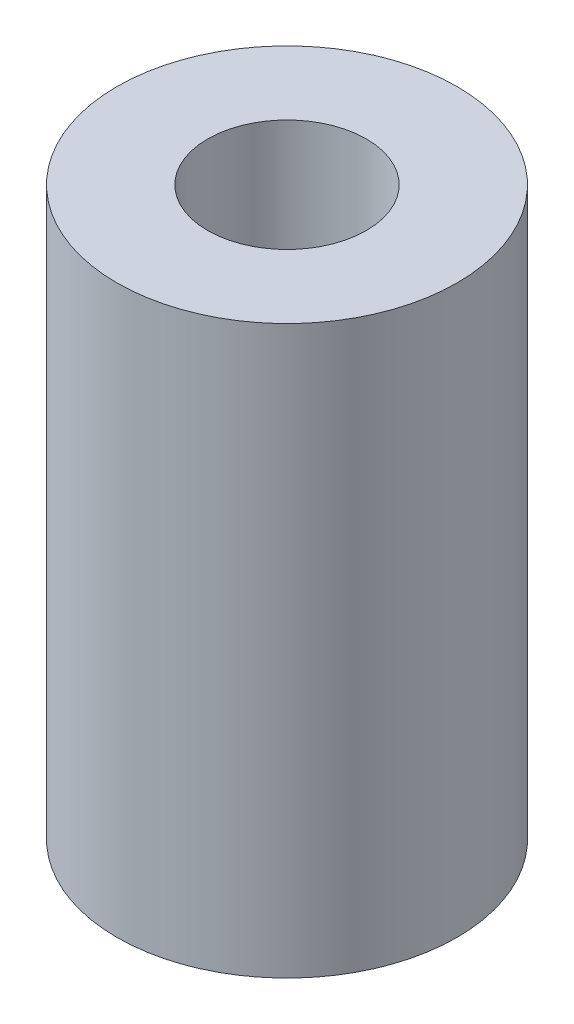
SolidWorks part; units mm, degrees
ref_plane "Front Plane" through (0, 0, 0) normal (0, 0, 1) x (1, 0, 0)
ref_plane "Top Plane" through (0, 0, 0) normal (0, 1, 0) x (1, 0, 0)
ref_plane "Right Plane" through (0, 0, 0) normal (1, 0, 0) x (0, 0, -1)
sketch "Esquisse1" plane through (0, 0, 0) normal (0, 1, 0) x (1, 0, 0)
  circle A0 centre (0, 0) radius 1.4
  circle A1 centre (0, 0) radius 3
extrude "Boss.-Extru.1" add sketch "Esquisse1" along normal blind 10
